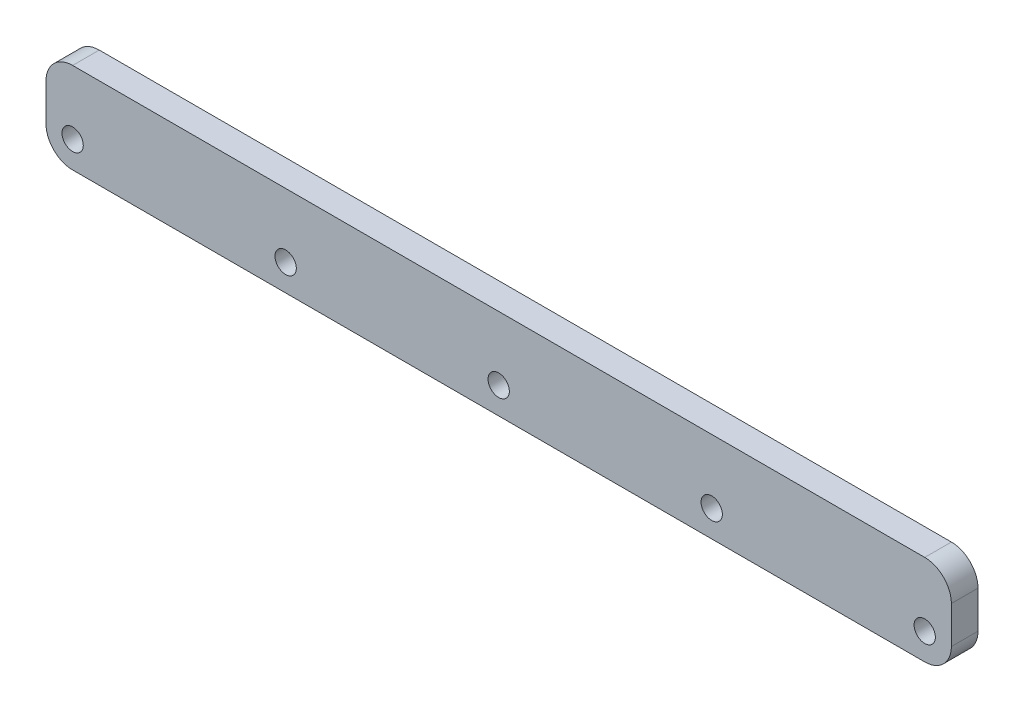
SolidWorks part; units mm, degrees
ref_plane "Plan de face" through (0, 0, 0) normal (0, 0, 1) x (1, 0, 0)
ref_plane "Plan de dessus" through (0, 0, 0) normal (0, 1, 0) x (1, 0, 0)
ref_plane "Plan de droite" through (0, 0, 0) normal (1, 0, 0) x (0, 0, -1)
sketch "Esquisse1" plane through (0, 0, 0) normal (0, 0, 1) x (1, 0, 0)
  line L0 (0, 5) -> (170, 5) construction
  line L1 (0, 0) -> (170, 0)
  line L2 (0, 0) -> (0, 17)
  line L3 (0, 17) -> (170, 17)
  line L4 (170, 0) -> (170, 17)
  circle A0 centre (5, 5) radius 2
  circle A1 centre (45, 5) radius 2
  circle A2 centre (85, 5) radius 2
  circle A3 centre (125, 5) radius 2
  circle A4 centre (165, 5) radius 2
  point P9 (176.2462, 0)
  dimension "D1" = 4
  dimension "D2" = 5
  dimension "D3" = 12
  dimension "D4" = 5
  dimension "D5" = 5
  dimension "D6" = 40
extrude "Boss.-Extru.1" add sketch "Esquisse1" along normal blind 5
fillet "Congé1" radius 5 4 edges at (170, 0, 2.5) (170, 17, 2.5) (0, 0, 2.5) (0, 17, 2.5)
